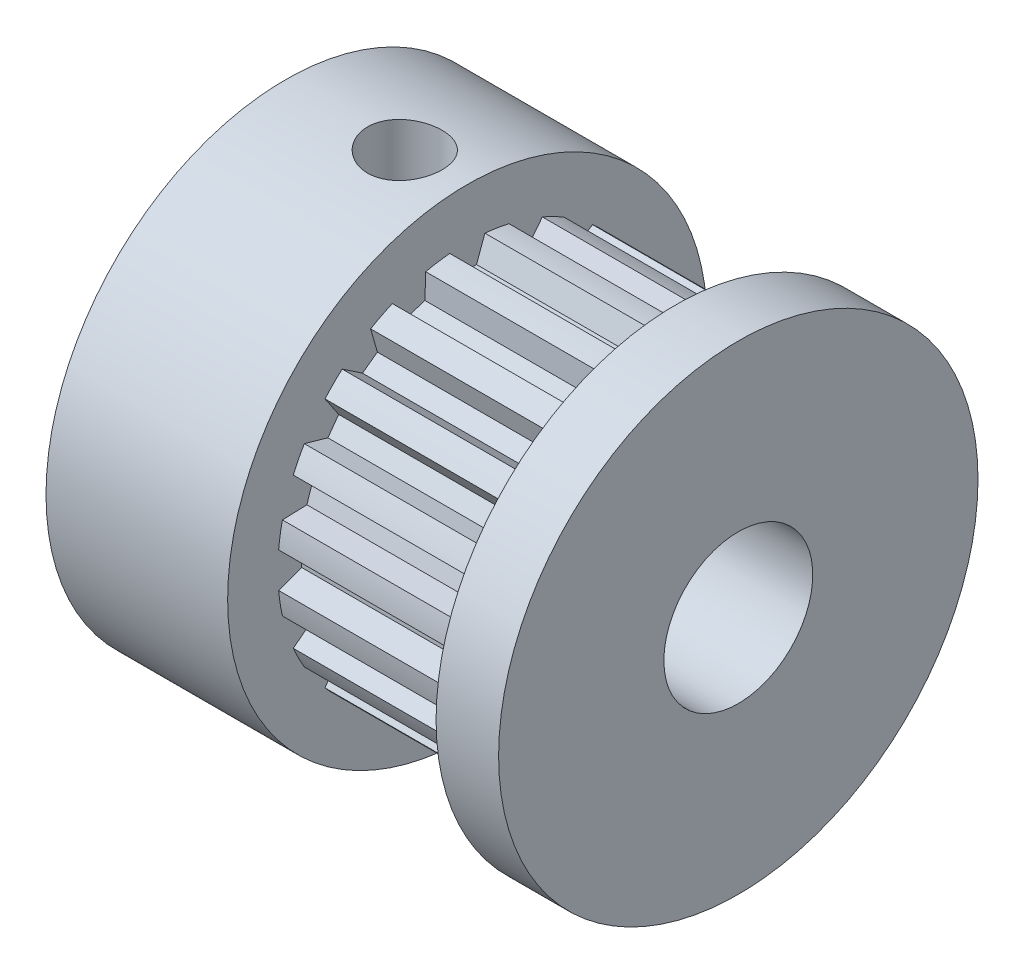
SolidWorks part; units mm, degrees
material "Aluminium"
ref_plane "Front Plane" through (0, 0, 0) normal (0, 0, 1) x (1, 0, 0)
ref_plane "Top Plane" through (0, 0, 0) normal (0, 1, 0) x (1, 0, 0)
ref_plane "Right Plane" through (0, 0, 0) normal (1, 0, 0) x (0, 0, -1)
sketch "Sketch1" plane through (0, 0, 0) normal (0, 0, 1) x (1, 0, 0)
  line L0 (0, 0) -> (6.7073, 0) construction
  line L1 (0, 2.5) -> (15.2, 2.5)
  line L2 (15.2, 2.5) -> (15.2, 8.05)
  line L3 (0, 2.5) -> (0, 8.05)
  line L4 (0, 8.05) -> (6.1, 8.05)
  line L5 (13.1, 8.05) -> (15.2, 8.05)
  line L8 (6.1, 8.05) -> (6.1, 6.365)
  line L9 (6.1, 6.365) -> (13.1, 6.365)
  line L10 (9.6, 6.365) -> (9.6, 6.1119) construction
  line L11 (13.1, 8.05) -> (13.1, 6.365)
  dimension "D1" = 5
  dimension "D2" = 6.1
  dimension "D3" = 7
  dimension "D4" = 16.1
  dimension "D5" = 12.73
  dimension "D6" = 15.2
revolve "Revolve1" add sketch "Sketch1" angle 360 about L0
hole_wizard "M3 Tapped Hole1" positions "3DSketch1" profile "Sketch2" tap size "M3" standard "ISO"
sketch3d "3DSketch1"
  line L0 (4, 8.05, 0) -> (0, 0, 0) construction
  line L1 (0, 0, 0) -> (0, 8.05, 0) construction
  line L2 (0, 8.05, 0) -> (4, 8.05, 0) construction
  point P0 (4, 8.05, 0)
  dimension "D1" = 4
sketch "Sketch2" plane through (4, 8.05, 0) normal (1, 0, 0) x (0, 0, 1)
  line L0 (0, 0) -> (0, 5.55)
  line L1 (0, 5.55) -> (1.25, 5.55)
  line L2 (1.25, 5.55) -> (1.25, 0)
  line L5 (1.25, 0) -> (0, 0)
  line L11 (0, -6.35) -> (0, 107.95) construction
  dimension "Thru Tap Drill Dia." = 2.5
  dimension "Thru Tap Drill Depth" = 5.55
cosmetic thread "Hole Thread1" parameters "D2"=3
ref_plane "Plane1" through (13.1, 0, 0) normal (-1, 0, 0) x (0, 0, 1)
sketch "Sketch3" plane through (13.1, 0, 0) normal (-1, 0, 0) x (0, 0, 1)
  line L0 (-0.6, 6.365) -> (-0.3088, 5.565)
  line L1 (-0.3088, 5.565) -> (0.3088, 5.565)
  line L2 (0.3088, 5.565) -> (0.6, 6.365)
  line L3 (0.6, 6.365) -> (-0.6, 6.365)
  line L4 (0, 6.365) -> (0, 0) construction
  circle A0 centre (0, 0) radius 6.365 construction
  dimension "D1" = 40
  dimension "D2" = 1.2
  dimension "D3" = 0.8
extrude "Cut-Extrude1" cut sketch "Sketch3" along normal blind 7
pattern_circular "CirPattern1" count 20 over 360 about axis through (0, 0, 0) along (1, 0, 0) of "Cut-Extrude1"
